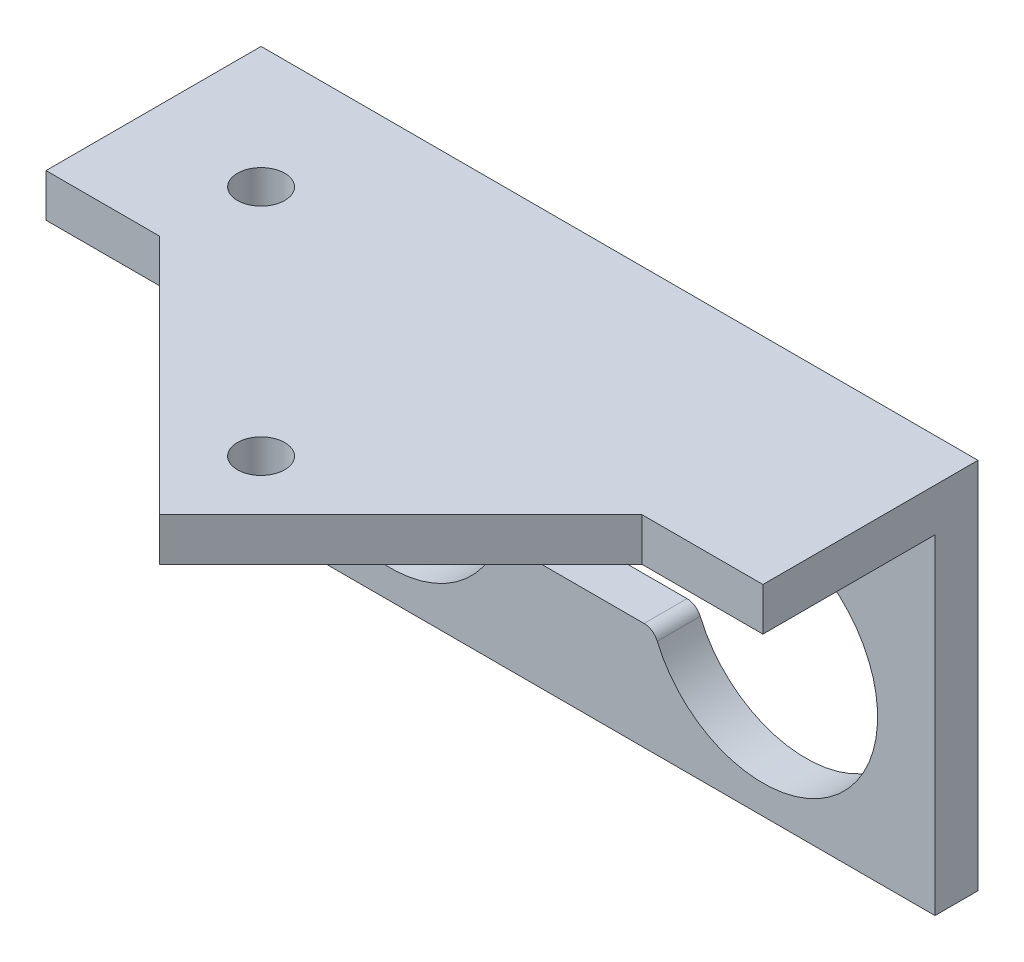
SolidWorks part; units mm, degrees
ref_plane "前视基准面" through (0, 0, 0) normal (0, 0, 1) x (1, 0, 0)
ref_plane "上视基准面" through (0, 0, 0) normal (0, 1, 0) x (1, 0, 0)
ref_plane "右视基准面" through (0, 0, 0) normal (1, 0, 0) x (0, 0, -1)
sketch "草图1" plane through (0, 0, 0) normal (0, 0, 1) x (1, 0, 0)
  line L1 (25, -10) -> (-25, -10)
  line L2 (25, -10) -> (25, 10)
  line L3 (25, 10) -> (-25, 10)
  line L4 (-25, -10) -> (-25, 10)
  line L5 (25, -10) -> (-25, 10) construction
  line L6 (25, 10) -> (-25, -10) construction
  line L8 (-4.7084, 2.5) -> (4.7084, 2.5)
  line L9 (4.7084, -2.5) -> (-4.7084, -2.5)
  line L10 (3.25, 7.25) -> (-3.25, 7.25) construction
  line L11 (3.25, 5.5) -> (-3.25, 5.5)
  line L12 (3.25, 9) -> (-3.25, 9)
  arc A7 (5.6297, -3.1111) -> (5.6297, 3.1111) centre (13, 0) ccw
  arc A8 (-5.6297, 3.1111) -> (-5.6297, -3.1111) centre (-13, 0) ccw
  arc A9 (4.7084, -2.5) -> (5.6297, -3.1111) centre (4.7084, -3.5) cw
  arc A10 (4.7084, 2.5) -> (5.6297, 3.1111) centre (4.7084, 3.5) ccw
  arc A11 (-4.7084, -2.5) -> (-5.6297, -3.1111) centre (-4.7084, -3.5) ccw
  arc A12 (-4.7084, 2.5) -> (-5.6297, 3.1111) centre (-4.7084, 3.5) cw
  arc A13 (3.25, 5.5) -> (3.25, 9) centre (3.25, 7.25) ccw
  arc A14 (-3.25, 9) -> (-3.25, 5.5) centre (-3.25, 7.25) ccw
  point P0 (0, 0)
  point P22 (0, 7.25)
  dimension "D3" = 1
  dimension "D4" = 8
  dimension "D5" = 8
  dimension "D6" = 2.5
  dimension "D8" = 13
  dimension "D9" = 13
  dimension "D12" = 1.75
  dimension "D1" = 20
  dimension "D2" = 50
  dimension "D7" = 2.5
  dimension "D10" = 7.25
  dimension "D11" = 6.5
  dimension "D13" = 3.25
extrude "凸台-拉伸1" add sketch "草图1" along normal blind 3
sketch "草图2" plane through (0, 10, 0) normal (0, 1, 0) x (1, 0, 0)
  line L1 (-25, 0) -> (25, 0)
  line L2 (-25, 0) -> (-25, -15)
  line L3 (-25, -15) -> (25, -15)
  line L4 (25, 0) -> (25, -15)
  dimension "D1" = 15
extrude "凸台-拉伸2" add sketch "草图2" along normal blind 6
sketch "草图5" plane through (0, 10, 0) normal (0, -1, 0) x (1, 0, 0)
  line L1 (25, 3) -> (-25, 3)
  line L2 (25, 3) -> (25, 15)
  line L3 (25, 15) -> (-25, 15)
  line L4 (-25, 3) -> (-25, 15)
extrude "切除-拉伸2" cut sketch "草图5" against normal blind 3
sketch "草图7" plane through (0, 16, 0) normal (0, 1, 0) x (1, 0, 0)
  line L4 (-0.2513, -31.8198) -> (-17.0711, -15)
  line L14 (-0.2513, -31.8198) -> (16.5685, -15)
  line L15 (-25, -15) -> (25, -15) construction
  line L16 (16.5685, -15) -> (-17.0711, -15)
  circle A1 centre (-0.2513, -24.7487) radius 1.65
  dimension "D5" = 3.3
  dimension "5" = 5
extrude "凸台-拉伸3" add sketch "草图7" against normal blind 3
sketch "草图8" plane through (0, 16, 0) normal (0, 1, 0) x (1, 0, 0)
  circle A0 centre (-16.5147, -8.4853) radius 1.65
  circle A1 centre (-0.2513, -24.7487) radius 1.65 construction
  dimension "D1" = 23
  dimension "D2" = 3.3
extrude "切除-拉伸3" cut sketch "草图8" against normal blind 3
